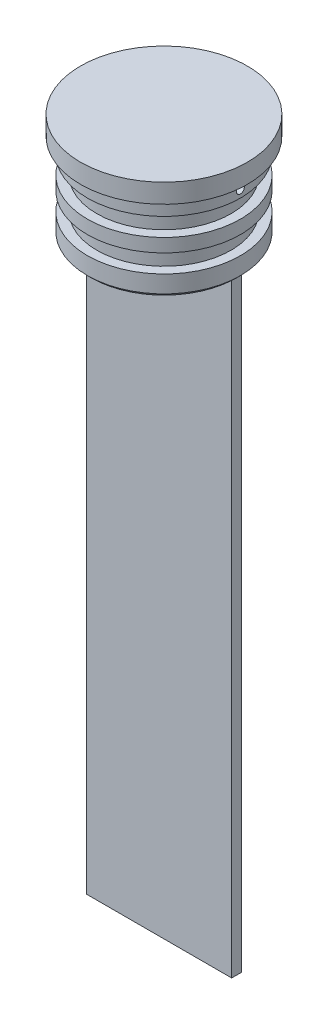
SolidWorks part; units mm, degrees
ref_plane "Front Plane" through (0, 0, 0) normal (0, 0, 1) x (1, 0, 0)
ref_plane "Top Plane" through (0, 0, 0) normal (0, 1, 0) x (1, 0, 0)
ref_plane "Right Plane" through (0, 0, 0) normal (1, 0, 0) x (0, 0, -1)
sketch "Sketch1" plane through (0, 0, 0) normal (0, 0, 1) x (1, 0, 0)
  line L0 (0, 20.3688) -> (0, -16.6557) construction
  line L1 (0, 13.97) -> (-11.049, 13.97)
  line L2 (-11.049, 13.97) -> (-11.049, 11.43)
  line L3 (-11.049, 11.43) -> (-10.1346, 11.43)
  line L4 (-10.1346, 11.43) -> (-10.1346, 9.398)
  line L5 (-10.1346, 0) -> (0, 0)
  line L6 (-10.1346, 9.398) -> (-8.89, 9.398)
  line L7 (-8.89, 9.398) -> (-8.89, 6.985)
  line L8 (-8.89, 6.985) -> (-10.1346, 6.985)
  line L9 (-10.1346, 5.207) -> (-8.89, 5.207)
  line L10 (-8.89, 5.207) -> (-8.89, 2.794)
  line L11 (-8.89, 2.794) -> (-10.1346, 2.794)
  line L12 (-10.1346, 6.985) -> (-10.1346, 5.207)
  line L13 (-10.1346, 2.794) -> (-10.1346, 0)
  line L14 (0, 13.97) -> (0, 0)
  point P15 (-11.049, 12.7)
other "AlignGroup1" parameters "D1"=19.5893, "D2"=5.7916, "D3"=20.6427, "D4"=10.414, "D5"=3.0397, "D6"=3.4421, "D7"=0.7504, "D8"=6.7982, "D9"=1.5008, "D10"=2.413
revolve "Revolve1" add sketch "Sketch1" angle 360 about L0
chamfer "Chamfer1" distance 0.508 angle 45 1 edges at (0, 0, 10.1346)
sketch "Sketch2" plane through (0, 0, 0) normal (0, -1, 0) x (1, 0, 0)
  line L0 (-10.1346, 0) -> (10.1346, 0) construction
  line L2 (-9.6056, 0.635) -> (9.6056, 0.635)
  line L3 (-9.6056, 0.635) -> (-9.6056, -0.635)
  line L4 (-9.6056, -0.635) -> (9.6056, -0.635)
  line L5 (9.6056, 0.635) -> (9.6056, -0.635)
  circle A0 centre (0, 0) radius 10.1346 construction
  circle A1 centre (0, 0) radius 9.6266 construction
  point P9 (-9.6056, 0)
  dimension "D1" = 1.27
extrude "Boss-Extrude1" add sketch "Sketch2" along normal blind 80.01
fillet "Fillet1" radius 0.127 1 edges at (0, 11.43, 10.1346)
sketch "Sketch3" plane through (0, 0, 0) normal (1, 0, 0) x (0, 0, -1)
  line L0 (-10.2616, 11.43) -> (10.2616, 11.43) construction
  circle A0 centre (0, 10.414) radius 0.5334
  dimension "D2" = 1.0668
  dimension "D1" = 1.016
extrude "Cut-Extrude1" cut sketch "Sketch3" against normal through all and the other way through all
